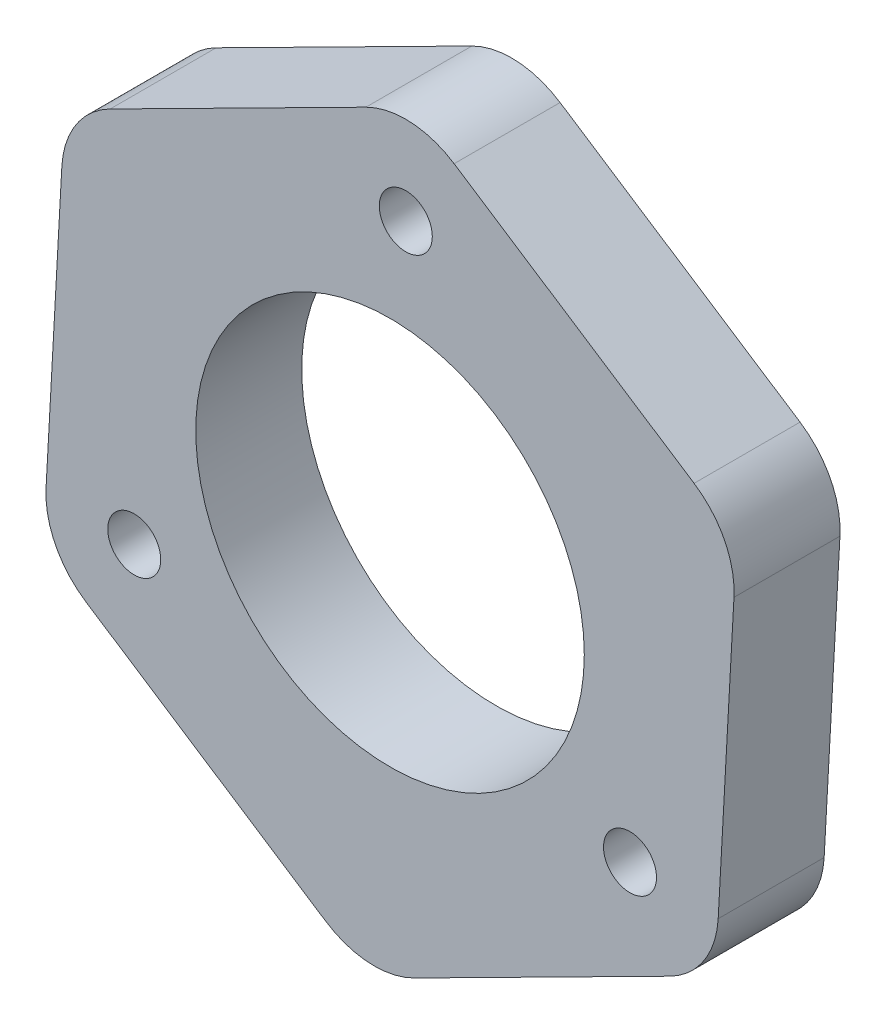
SolidWorks part; units mm, degrees
ref_plane "Front Plane" through (0, 0, 0) normal (0, 0, 1) x (1, 0, 0)
ref_plane "Top Plane" through (0, 0, 0) normal (0, 1, 0) x (1, 0, 0)
ref_plane "Right Plane" through (0, 0, 0) normal (1, 0, 0) x (0, 0, -1)
sketch "Sketch1" plane through (0, 0, 0) normal (0, 0, 1) x (1, 0, 0)
  line L0 (-179.9714, 291.2832) -> (-141.916, 289.1838) construction
  line L6 (-159.5795, 269.5659) -> (-145.0983, 276.8944)
  line L7 (-178.1603, 278.7183) -> (-164.573, 269.8414)
  line L8 (-142.363, 281.0811) -> (-141.469, 297.2865)
  line L9 (-179.5244, 299.3858) -> (-180.4184, 283.1805)
  line L10 (-143.7271, 301.7487) -> (-157.3144, 310.6256)
  line L11 (-162.3079, 310.901) -> (-176.7891, 303.5726)
  arc A0 (-178.1603, 278.7183) -> (-180.4184, 283.1805) centre (-175.425, 282.905) cw
  arc A1 (-164.573, 269.8414) -> (-159.5795, 269.5659) centre (-161.8377, 274.0281) ccw
  arc A2 (-145.0983, 276.8944) -> (-142.363, 281.0811) centre (-147.3564, 281.3566) ccw
  arc A3 (-141.469, 297.2865) -> (-143.7271, 301.7487) centre (-146.4624, 297.5619) ccw
  arc A4 (-157.3144, 310.6256) -> (-162.3079, 310.901) centre (-160.0497, 306.4388) ccw
  circle A5 centre (-147.3564, 281.3566) radius 1.5
  circle A6 centre (-160.0497, 306.4388) radius 1.5
  circle A7 centre (-175.425, 282.905) radius 1.5
  arc A8 (-179.5244, 299.3858) -> (-176.7891, 303.5726) centre (-174.531, 299.1104) cw
  circle A9 centre (-160.9437, 290.2335) radius 11
  dimension "D1" = 3
  dimension "D2" = 38.1133
  dimension "D11" = 5.0011
  dimension "D16" = 22
  dimension "D3" = 16.23
  dimension "D4" = 60
  dimension "D5" = 60
  dimension "D6" = 60
  dimension "D7" = 60
  dimension "D8" = 60
  dimension "D9" = 5.0011
  dimension "D10" = 5.0011
  dimension "D12" = 269.5659
  dimension "D13" = 159.5795
  dimension "D14" = 312.5769
  dimension "D15" = 8.115
extrude "Boss-Extrude1" add sketch "Sketch1" along normal blind 6 separate body
